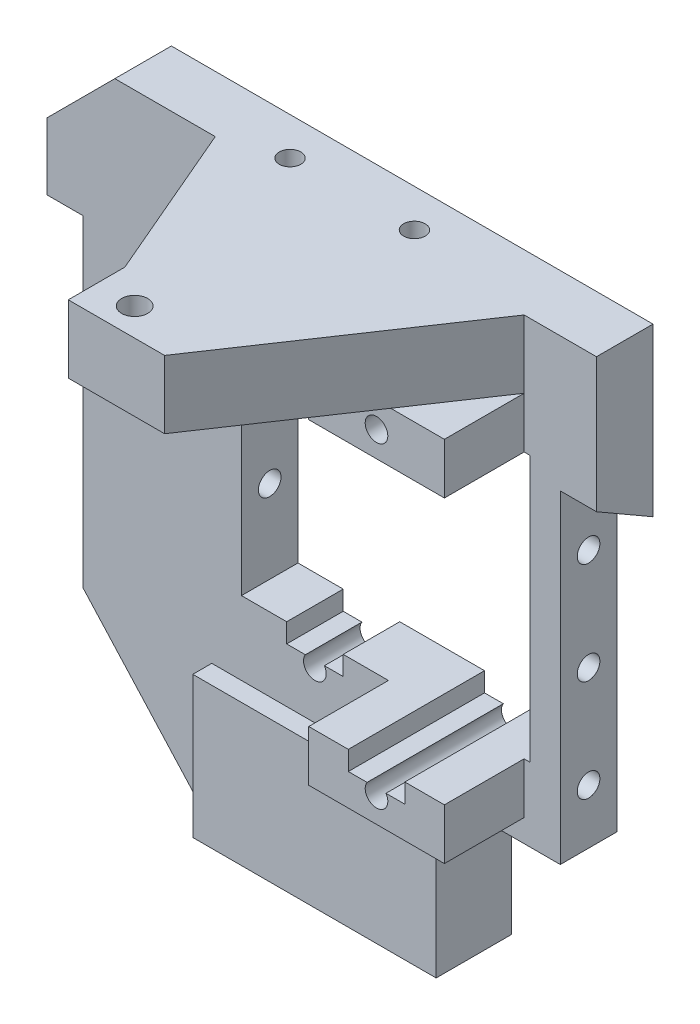
SolidWorks part; units mm, degrees
ref_plane "前视基准面" through (0, 0, 0) normal (0, 0, 1) x (1, 0, 0)
ref_plane "上视基准面" through (0, 0, 0) normal (0, 1, 0) x (1, 0, 0)
ref_plane "右视基准面" through (0, 0, 0) normal (1, 0, 0) x (0, 0, -1)
sketch "草图1" plane through (0, 0, 0) normal (0, 0, 1) x (1, 0, 0)
  line L0 (24.6404, 26.5965) -> (-17.9596, 26.5965)
  line L1 (-17.9596, 26.5965) -> (-23.9596, 20.5965)
  line L2 (-23.9596, 20.5965) -> (-23.9596, 11.8052)
  line L3 (-23.9596, 11.8052) -> (-20.7596, 11.8052)
  line L4 (-20.7596, 11.8052) -> (-20.7596, -13.8347)
  line L5 (-20.7596, -13.8347) -> (-9.3856, -26.4035)
  line L6 (-9.3856, -26.4035) -> (12.1404, -26.4035)
  line L7 (12.1404, -26.4035) -> (12.1404, -13.9035)
  line L8 (12.1404, -13.9035) -> (21.4404, -13.9035)
  line L9 (21.4404, -13.9035) -> (21.4404, 11.8351)
  line L10 (21.4404, 11.8351) -> (24.6404, 11.8351)
  line L11 (24.6404, 11.8351) -> (24.6404, 26.5965)
  line L12 (-6.7596, 16.0965) -> (18.7404, 16.0965)
  line L13 (18.7404, 16.0965) -> (18.7404, -7.4035)
  line L14 (18.7404, -7.4035) -> (14.7404, -7.4035)
  line L15 (14.7404, -7.4035) -> (14.7404, -9.1035)
  line L16 (14.7404, -9.1035) -> (9.7404, -9.1035) construction
  line L17 (9.7404, -9.1035) -> (9.7404, -7.4035)
  line L18 (9.7404, -7.4035) -> (2.2404, -7.4035)
  line L19 (2.2404, -7.4035) -> (2.2404, -9.1035)
  line L20 (2.2404, -9.1035) -> (-2.7596, -9.1035) construction
  line L21 (-2.7596, -9.1035) -> (-2.7596, -7.4035)
  line L22 (-2.7596, -7.4035) -> (-6.7596, -7.4035)
  line L23 (-6.7596, -7.4035) -> (-6.7596, 16.0965)
  line L24 (-0.2653, 18.3465) -> (12.2347, 18.3465) construction
  line L25 (-0.2653, -9.6535) -> (12.2347, -9.6535) construction
  line L26 (-0.2653, -9.6535) -> (-0.2596, -9.1035) construction
  line L27 (-2.7596, -9.1035) -> (-1.1053, -9.1035)
  line L28 (0.5747, -9.1035) -> (2.2404, -9.1035)
  line L29 (9.7404, -9.1035) -> (11.3995, -9.1035)
  line L30 (13.0699, -9.1035) -> (14.7404, -9.1035)
  circle A0 centre (12.2347, 18.3465) radius 1
  circle A1 centre (12.2347, -9.6535) radius 1 construction
  circle A2 centre (-0.2653, -9.6535) radius 1.004 construction
  circle A3 centre (-0.2653, 18.3465) radius 1
  circle A4 centre (12.2347, 18.3465) radius 1
  arc A5 (-1.1053, -9.1035) -> (0.5747, -9.1035) centre (-0.2653, -9.6535) ccw
  arc A6 (11.3995, -9.1035) -> (13.0699, -9.1035) centre (12.2347, -9.6535) ccw
  dimension "D1" = 28
  dimension "D2" = 0.55
  dimension "D3" = 5
  dimension "D4" = 7.5
  dimension "D5" = 4
  dimension "D6" = 1.7
  dimension "D7" = 23.5
  dimension "D8" = 2.7
  dimension "D9" = 14
  dimension "D10" = 10.5
  dimension "D11" = 19
  dimension "D12" = 3.2
  dimension "D13" = 9.3
  dimension "D14" = 12.5
extrude "凸台-拉伸1" add sketch "草图1" along normal blind 5 contours L10 L11 L0 L1 L2 L3 L4 L5 L6 L7 L8 L9 A6 L29 L17 L18 L19 L28 A5 L27 L21 L22 L23 L12 L13 L14 L15 L30 A3 A0
sketch "草图2" plane through (0, 0, 5) normal (0, 0, 1) x (1, 0, 0)
  line L0 (12.1404, -13.9035) -> (21.4404, -13.9035) construction
  line L1 (12.1404, -26.4035) -> (-9.3856, -26.4035)
  line L2 (12.1404, -26.4035) -> (12.1404, -13.9035)
  line L3 (12.1404, -13.9035) -> (-9.3856, -13.9035)
  line L4 (-9.3856, -26.4035) -> (-9.3856, -13.9035)
extrude "凸台-拉伸2" add sketch "草图2" along normal blind 1.68
sketch "草图3" plane through (0, -26.4035, 0) normal (0, -1, 0) x (1, 0, 0)
  line L0 (-4.1226, 3.34) -> (6.8774, 3.34) construction
  line L1 (-4.1226, 3.34) -> (-9.3856, 3.34) construction
  line L2 (-9.3856, 5) -> (-9.3856, 0) construction
  line L3 (6.8774, 3.34) -> (12.1404, 3.34) construction
  line L4 (12.1404, 6.68) -> (12.1404, 0) construction
  line L5 (6.8774, 3.34) -> (6.8774, 6.68) construction
  line L6 (-9.3856, 6.68) -> (12.1404, 6.68) construction
  line L7 (6.8774, 3.34) -> (6.8774, 0) construction
  line L8 (-9.3856, 0) -> (12.1404, 0) construction
  circle A0 centre (-4.1226, 3.34) radius 0.95
  circle A1 centre (6.8774, 3.34) radius 0.95
  dimension "D2" = 1.9
  dimension "D1" = 11
extrude "切除-拉伸1" cut sketch "草图3" against normal blind 5
sketch "草图4" plane through (0, 0, 5) normal (0, 0, 1) x (1, 0, 0)
  line L0 (14.7404, -7.4035) -> (14.7404, -9.1035) construction
  line L1 (9.7404, -7.4035) -> (2.2404, -7.4035) construction
  line L2 (6.2404, -7.4035) -> (18.2404, -7.4035) construction
  line L3 (6.2404, -7.4035) -> (6.2404, -11.9035)
  line L4 (6.2404, -11.9035) -> (18.2404, -11.9035)
  line L5 (18.2404, -7.4035) -> (18.2404, -11.9035)
  line L6 (9.7404, -9.1035) -> (9.7404, -7.4035) construction
  line L7 (9.7404, -7.4035) -> (9.7404, -9.1035)
  line L8 (9.7404, -9.1035) -> (11.3995, -9.1035)
  line L9 (13.0699, -9.1035) -> (14.7404, -9.1035)
  line L10 (14.7404, -9.1035) -> (14.7404, -7.4035)
  line L11 (6.2404, -7.4035) -> (9.7404, -7.4035)
  line L12 (14.7404, -7.4035) -> (18.2404, -7.4035)
  line L13 (-6.7596, 16.0965) -> (18.7404, 16.0965) construction
  line L14 (18.2404, 16.0965) -> (6.2404, 16.0965)
  line L15 (18.2404, 16.0965) -> (18.2404, 20.5965)
  line L16 (18.2404, 20.5965) -> (6.2404, 20.5965)
  line L17 (6.2404, 16.0965) -> (6.2404, 20.5965)
  arc A0 (11.3995, -9.1035) -> (13.0699, -9.1035) centre (12.2347, -9.6535) ccw
  circle A1 centre (12.2347, 18.3465) radius 1
  point P8 (9.7404, -8.2535)
  dimension "D1" = 3.5
  dimension "D2" = 3.5
  dimension "D3" = 4.5
extrude "凸台-拉伸3" add sketch "草图4" along normal blind 7.05
sketch "草图5" plane through (0, 20.5965, 0) normal (0, 1, 0) x (1, 0, 0)
  line L1 (18.2404, 0) -> (5.4404, 19) construction
  line L2 (5.4404, 19) -> (-6.425, 19) construction
  line L3 (-3.0776, 14) -> (-3.0776, 19) construction
  line L7 (-3.0776, 14) -> (-9.0776, 0) construction
  line L9 (-9.0776, 0) -> (18.2404, 0) construction
  line L11 (18.2404, -5) -> (18.2404, 0)
  line L13 (18.2404, -2.5) -> (16.3621, -2.5) construction
  line L14 (-3.0776, -19) -> (-3.0776, -24)
  line L15 (-9.0776, -5) -> (18.2404, -5)
  line L16 (-3.0776, -19) -> (-9.0776, -5)
  line L17 (18.2404, -5) -> (5.4404, -24)
  line L18 (-3.0776, -24) -> (5.4404, -24)
  circle A2 centre (0.3287, 16.5351) radius 1.15 construction
  circle A3 centre (0.3287, -21.5351) radius 1.15
  line M1 (18.2404, -5) -> (6.2404, -5)
  line M2 (6.2404, -5) -> (6.2404, -12.05)
  line M3 (6.2404, -12.05) -> (18.2404, -12.05)
  dimension "D1" = 3.4062
extrude "凸台-拉伸4" add sketch "草图5" along normal blind 6 contours L14 L18 L17 L15 L16 A3 M3 M2 | L17 M1 M2 M3
ref_plane "基准面1" through (0, 4.3465, 0) normal (0, 1, 0) x (1, 0, 0)
sketch "草图6" plane through (0, 26.5965, 0) normal (0, 1, 0) x (1, 0, 0)
  circle A0 centre (-4.1226, -3.34) radius 0.95
  circle A1 centre (6.8774, -3.34) radius 0.95
extrude "切除-拉伸2" cut sketch "草图6" against normal blind 5
sketch "草图7" plane through (21.4404, 0, 0) normal (1, 0, 0) x (0, 0, -1)
  line L0 (-2.5, 11.8351) -> (-2.5, 8.9351) construction
  line L1 (-5, 11.8351) -> (0, 11.8351) construction
  line L2 (-2.5, 8.9351) -> (-2.5, -0.0649) construction
  line L3 (-2.5, -0.0649) -> (-2.5, -9.0649) construction
  circle A0 centre (-2.5, 8.9351) radius 1
  circle A1 centre (-2.5, -0.0649) radius 1
  circle A2 centre (-2.5, -9.0649) radius 1
  dimension "D1" = 2.9
  dimension "D2" = 9
  dimension "D3" = 9
extrude "切除-拉伸3" cut sketch "草图7" against normal blind 100 contours A0 | A1
sketch "草图8" plane through (21.4404, 0, 0) normal (1, 0, 0) x (0, 0, -1)
  line L0 (-2.5, -0.0649) -> (-2.5, -9.0649) construction
  circle A0 centre (-2.5, -9.0649) radius 1
extrude "切除-拉伸4" cut sketch "草图8" against normal blind 3
sketch "草图9" plane through (-20.7596, 0, 0) normal (-1, 0, 0) x (0, 0, 1)
  line L0 (2.5, -0.0649) -> (2.5, -9.0649) construction
  circle A0 centre (2.5, -9.0649) radius 1
extrude "切除-拉伸5" cut sketch "草图9" against normal blind 3
sketch "草图10" plane through (-23.9596, 0, 0) normal (-1, 0, 0) x (0, 0, 1)
  line L3 (5, 11.8052) -> (0, 11.8052)
  line L4 (0, 11.8052) -> (5, 14.6919)
  line L5 (5, 20.5965) -> (5, 11.8052) construction
  line L6 (0, 11.8052) -> (0, 8.4487) construction
  line L7 (5, 11.8052) -> (5, 14.6919)
  dimension "D1" = 240
extrude "切除-拉伸6" cut sketch "草图10" against normal blind 3.2
sketch "草图11" plane through (24.6404, 0, 0) normal (1, 0, 0) x (0, 0, -1)
  line L0 (0, 11.8351) -> (-5, 14.7218)
  line L1 (-5, 11.8351) -> (-5, 26.5965) construction
  line L2 (-5, 14.7218) -> (-5, 11.8351)
  line L3 (-5, 11.8351) -> (0, 11.8351)
  line L4 (0, 11.8351) -> (0, 7.1907) construction
  dimension "D1" = 240
extrude "切除-拉伸7" cut sketch "草图11" against normal blind 3.2
